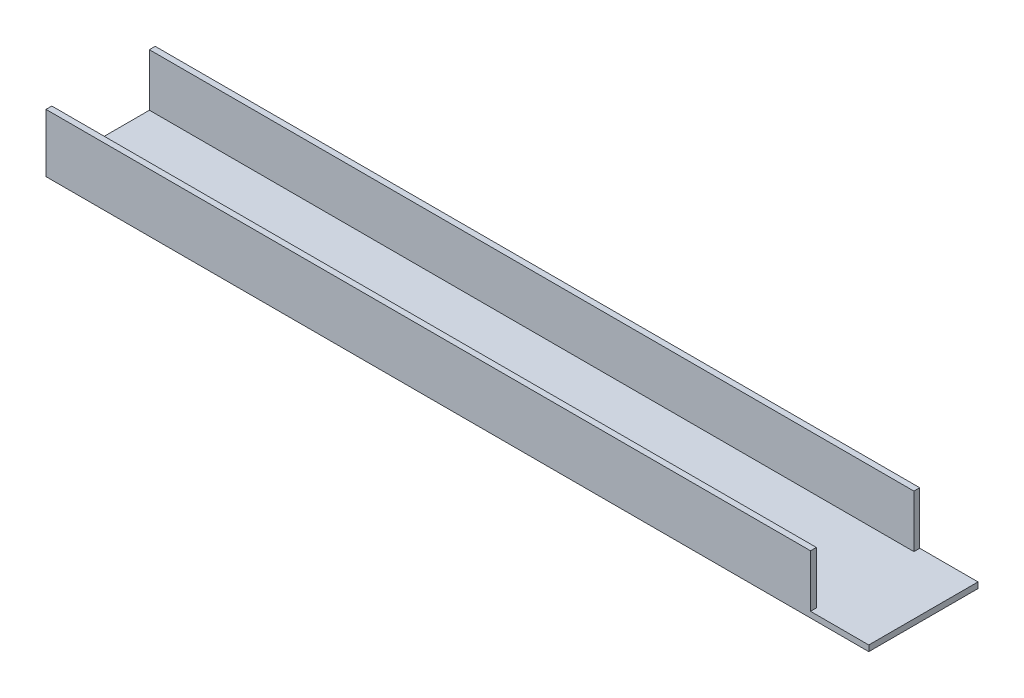
SolidWorks part; units mm, degrees
ref_plane "정면" through (0, 0, 0) normal (0, 0, 1) x (1, 0, 0)
ref_plane "윗면" through (0, 0, 0) normal (0, 1, 0) x (1, 0, 0)
ref_plane "우측면" through (0, 0, 0) normal (1, 0, 0) x (0, 0, -1)
sketch "스케치1" plane through (0, 0, 0) normal (0, 1, 0) x (1, 0, 0)
  line L1 (0, 0) -> (565, 0)
  line L2 (0, 0) -> (0, 75)
  line L3 (0, 75) -> (565, 75)
  line L4 (565, 0) -> (565, 75)
  dimension "D1" = 565
  dimension "D2" = 75
extrude "보스-돌출1" add sketch "스케치1" along normal blind 4
sketch "스케치2" plane through (0, 4, 0) normal (0, 1, 0) x (1, 0, 0)
  line L0 (565, 75) -> (0, 75) construction
  line L1 (0, 0) -> (525, 0)
  line L2 (0, 0) -> (0, 4)
  line L3 (0, 4) -> (525, 4)
  line L4 (525, 0) -> (525, 4)
  line L5 (525, 75) -> (0, 75)
  line L6 (525, 75) -> (525, 71)
  line L7 (525, 71) -> (0, 71)
  line L8 (0, 75) -> (0, 71)
  line L9 (0, 75) -> (0, 0) construction
  dimension "D1" = 4
  dimension "D2" = 4
  dimension "D3" = 525
extrude "보스-돌출2" add sketch "스케치2" along normal blind 36
